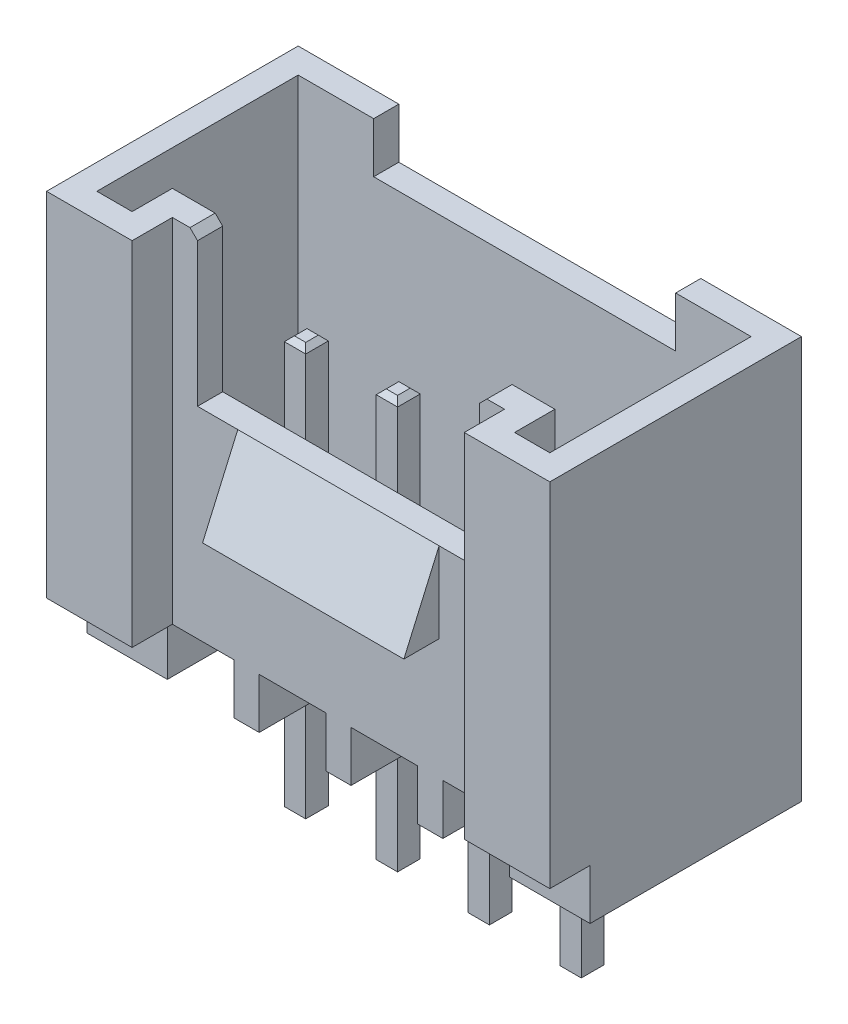
SolidWorks part; units mm, degrees
ref_plane "Plan de face" through (0, 0, 0) normal (0, 0, 1) x (1, 0, 0)
ref_plane "Plan de dessus" through (0, 0, 0) normal (0, 1, 0) x (1, 0, 0)
ref_plane "Plan de droite" through (0, 0, 0) normal (1, 0, 0) x (0, 0, -1)
sketch "Esquisse1" plane through (0, 0, 0) normal (0, 1, 0) x (1, 0, 0)
  line L1 (0, 0) -> (10, 0)
  line L2 (0, 0) -> (0, 5)
  line L3 (0, 5) -> (10, 5)
  line L4 (10, 0) -> (10, 5)
  dimension "D1" = 5
  dimension "D2" = 10
extrude "Boss.-Extru.1" add sketch "Esquisse1" along normal blind 8
sketch "Esquisse2" plane through (0, 8, 0) normal (0, 1, 0) x (1, 0, 0)
  line L0 (0, 0) -> (10, 0) construction
  line L1 (1.7, 0) -> (8.3, 0)
  line L2 (1.7, 0) -> (1.7, 0.8)
  line L3 (1.7, 0.8) -> (8.3, 0.8)
  line L4 (8.3, 0) -> (8.3, 0.8)
  line L5 (0, 5) -> (0, 0) construction
  line L6 (10, 0) -> (10, 5) construction
  dimension "D1" = 1.7
  dimension "D2" = 1.7
  dimension "D3" = 0.8
extrude "Enlèv. mat.-Extru.1" cut sketch "Esquisse2" against normal blind 8
sketch "Esquisse4" plane through (0, 8, 0) normal (0, 1, 0) x (1, 0, 0)
  line L16 (0.5, 0.5) -> (1.2, 0.5)
  line L17 (1.2, 0.5) -> (1.2, 1.3)
  line L18 (1.2, 1.3) -> (8.8, 1.3)
  line L19 (8.8, 1.3) -> (8.8, 0.5)
  line L20 (8.8, 0.5) -> (9.5, 0.5)
  line L21 (9.5, 0.5) -> (9.5, 4.5)
  line L22 (9.5, 4.5) -> (0.5, 4.5)
  line L23 (0.5, 4.5) -> (0.5, 0.5)
  line L24 (0.5, 0.5) -> (1.2, 0.5)
  line L25 (1.2, 0.5) -> (1.2, 1.3)
  line L26 (1.2, 1.3) -> (8.8, 1.3)
  line L27 (8.8, 1.3) -> (8.8, 0.5)
  line L28 (8.8, 0.5) -> (9.5, 0.5)
  line L29 (9.5, 0.5) -> (9.5, 4.5)
  line L30 (9.5, 4.5) -> (0.5, 4.5)
  line L31 (0.5, 4.5) -> (0.5, 0.5)
  dimension "D1" = 0.5
extrude "Enlèv. mat.-Extru.2" cut sketch "Esquisse4" against normal blind 6.5
sketch "Esquisse5" plane through (0, 8, 0) normal (0, 1, 0) x (1, 0, 0)
  line L0 (10, 5) -> (0, 5) construction
  line L1 (2, 5) -> (8, 5)
  line L2 (2, 5) -> (2, 4.5)
  line L3 (2, 4.5) -> (8, 4.5)
  line L4 (8, 5) -> (8, 4.5)
  line L5 (9.5, 4.5) -> (0.5, 4.5) construction
  line L6 (10, 0) -> (10, 5) construction
  line L7 (0, 5) -> (0, 0) construction
  dimension "D1" = 2
  dimension "D2" = 2
extrude "Enlèv. mat.-Extru.3" cut sketch "Esquisse5" against normal blind 1
sketch "Esquisse6" plane through (0, 8, 0) normal (0, 1, 0) x (1, 0, 0)
  line L0 (1.2, 1.3) -> (8.8, 1.3) construction
  line L1 (2.2, 1.3) -> (7.8, 1.3)
  line L2 (2.2, 1.3) -> (2.2, 0.8)
  line L3 (2.2, 0.8) -> (7.8, 0.8)
  line L4 (7.8, 1.3) -> (7.8, 0.8)
  line L5 (8.3, 0.8) -> (1.7, 0.8) construction
  line L6 (10, 0) -> (10, 5) construction
  line L7 (0, 5) -> (0, 0) construction
  dimension "D1" = 2.2
  dimension "D2" = 2.2
extrude "Enlèv. mat.-Extru.4" cut sketch "Esquisse6" against normal blind 3
sketch "Esquisse7" plane through (10, 0, 0) normal (1, 0, 0) x (0, 0, -1)
  line L1 (0, 0) -> (0.8, 0)
  line L2 (0, 0) -> (0, 1)
  line L3 (0, 1) -> (0.8, 1)
  line L4 (0.8, 0) -> (0.8, 1)
  dimension "D1" = 0.8
  dimension "D2" = 1
extrude "Enlèv. mat.-Extru.5" cut sketch "Esquisse7" against normal blind 10
sketch "Esquisse8" plane through (0, 0, 0) normal (0, -1, 0) x (1, 0, 0)
  line L0 (10, -0.8) -> (0, -0.8) construction
  line L1 (1.6, -0.8) -> (8.4, -0.8)
  line L2 (1.6, -0.8) -> (1.6, -5)
  line L3 (1.6, -5) -> (8.4, -5)
  line L4 (8.4, -0.8) -> (8.4, -5)
  line L5 (10, -5) -> (0, -5) construction
  line L6 (0, -5) -> (0, -0.8) construction
  line L7 (10, -0.8) -> (10, -5) construction
  dimension "D1" = 1.6
  dimension "D2" = 1.6
extrude "Enlèv. mat.-Extru.6" cut sketch "Esquisse8" against normal blind 1
sketch "Esquisse9" plane through (1.6, 0, 0) normal (1, 0, 0) x (0, 0, -1)
  line L0 (5, 1) -> (0.8, 1) construction
  line L1 (4.7, 1) -> (3.9, 0.2)
  line L2 (3.9, 0.2) -> (1.9, 0.2)
  line L3 (1.9, 0.2) -> (1.1, 1)
  line L4 (0.8, 0) -> (5, 0) construction
  line L5 (4.7, 1) -> (1.1, 1)
  dimension "D1" = 45
  dimension "D2" = 45
  dimension "D3" = 0.2
  dimension "D4" = 0.3
  dimension "D5" = 0.3
extrude "Boss.-Extru.2" add sketch "Esquisse9" along normal blind 6.8
ref_plane "Plan1" through (5, 0, 0) normal (1, 0, 0) x (0, 0, -1)
sketch "Esquisse11" plane through (5, 0, 0) normal (1, 0, 0) x (0, 0, -1)
  line L0 (0.8, 5) -> (0.1, 3.4)
  line L1 (0.1, 3.4) -> (0.8, 3.4)
  line L2 (0.8, 1) -> (0.8, 8) construction
  line L3 (0.8, 3.4) -> (0.8, 5)
  dimension "D1" = 1.6
  dimension "D2" = 0.7
extrude "Boss.-Extru.3" add sketch "Esquisse11" along normal blind 2 and the other way blind 2
ref_plane "Plan2" through (0, 1, 0) normal (0, 1, 0) x (1, 0, 0)
sketch "Esquisse12" plane through (0, 1, 0) normal (0, 1, 0) x (1, 0, 0)
  line L0 (8.3, 0.8) -> (1.7, 0.8) construction
  line L1 (1.6, 5) -> (8.4, 5) construction
  line L2 (3, 0.8) -> (7, 0.8) construction
  line L3 (4.75, 0.8) -> (5.25, 0.8)
  line L4 (4.75, 0.8) -> (4.75, 5)
  line L5 (4.75, 5) -> (5.25, 5)
  line L6 (5.25, 0.8) -> (5.25, 5)
  line L8 (2.925, 0.8) -> (3.425, 0.8)
  line L9 (2.925, 0.8) -> (2.925, 5)
  line L10 (2.925, 5) -> (3.425, 5)
  line L11 (3.425, 0.8) -> (3.425, 5)
  line L12 (6.575, 0.8) -> (7.075, 0.8)
  line L13 (6.575, 0.8) -> (6.575, 5)
  line L14 (6.575, 5) -> (7.075, 5)
  line L15 (7.075, 0.8) -> (7.075, 5)
  line L16 (3.175, 0.8) -> (3.175, 5) construction
  line L17 (6.825, 0.8) -> (6.825, 5) construction
  point P0 (5, 0.8)
  point P1 (5, 5)
  point P26 (6.2379, 5.3568)
  point P27 (6.2497, 5)
  dimension "D1" = 0.5
  dimension "D2" = 0.25
  dimension "D3" = 0.5
  dimension "D4" = 0.5
  dimension "D5" = 0.25
  dimension "D6" = 0.25
  dimension "D7" = 1.575
  dimension "D8" = 1.575
extrude "Boss.-Extru.4" add sketch "Esquisse12" against normal blind 1
chamfer "Chanfrein1" distance 0.15 angle 45 2 edges at (2.2, 8, -1.05) (7.8, 8, -1.05)
sketch "Esquisse13" plane through (0, 0.2, 0) normal (0, -1, 0) x (1, 0, 0)
  line L0 (5, -0.8) -> (5, -5) construction
  line L1 (2.05, -2.675) -> (2.475, -2.675)
  line L2 (2.05, -2.675) -> (2.05, -3.125)
  line L3 (2.05, -3.125) -> (2.475, -3.125)
  line L4 (2.475, -2.675) -> (2.475, -3.125)
  line L5 (4.3, -3.125) -> (3.875, -3.125)
  line L6 (3.875, -2.675) -> (3.875, -3.125)
  line L7 (4.3, -2.675) -> (4.3, -3.125)
  line L8 (4.3, -2.675) -> (3.875, -2.675)
  line L9 (4.75, -0.8) -> (5.25, -0.8) construction
  line L10 (5.25, -5) -> (4.75, -5) construction
  line L11 (1.6, -0.8) -> (1.6, -5) construction
  line L12 (2.925, -5) -> (2.925, -0.8) construction
  line L14 (2.05, -2.9) -> (2.475, -2.9) construction
  line L15 (2.925, -1.9) -> (1.6, -1.9) construction
  line L16 (3.175, -0.8) -> (3.175, -5) construction
  line L17 (2.925, -0.8) -> (3.425, -0.8) construction
  line L18 (3.425, -5) -> (2.925, -5) construction
  line L19 (5.7, -3.125) -> (6.125, -3.125)
  line L20 (5.7, -2.675) -> (5.7, -3.125)
  line L21 (5.7, -2.675) -> (6.125, -2.675)
  line L22 (6.125, -2.675) -> (6.125, -3.125)
  line L23 (7.525, -2.675) -> (7.525, -3.125)
  line L24 (7.95, -3.125) -> (7.525, -3.125)
  line L25 (7.95, -2.675) -> (7.95, -3.125)
  line L26 (7.95, -2.675) -> (7.525, -2.675)
  dimension "D1" = 0.45
  dimension "D2" = 0.45
  dimension "D3" = 0.45
  dimension "D4" = 1
extrude "Boss.-Extru.5" add sketch "Esquisse13" along normal blind 3.2 and the other way blind 5
chamfer "Chanfrein2" distance 0.1 angle 45 32 edges at (2.2625, -3, -3.125) (2.475, -3, -2.9) (2.05, -3, -2.9) (2.2625, -3, -2.675) (4.0875, -3, -3.125) (4.3, -3, -2.9) (4.0875, -3, -2.675) (3.875, -3, -2.9) (5.9125, -3, -3.125) (6.125, -3, -2.9) (5.9125, -3, -2.675) (5.7, -3, -2.9) (7.7375, -3, -3.125) (7.95, -3, -2.9) (7.525, -3, -2.9) (7.7375, -3, -2.675) (7.7375, 5.2, -2.675) (7.95, 5.2, -2.9) (7.525, 5.2, -2.9) (7.7375, 5.2, -3.125) (5.9125, 5.2, -2.675) (6.125, 5.2, -2.9) (5.9125, 5.2, -3.125) (5.7, 5.2, -2.9) (4.0875, 5.2, -2.675) (4.3, 5.2, -2.9) (4.0875, 5.2, -3.125) (3.875, 5.2, -2.9) (2.05, 5.2, -2.9) (2.2625, 5.2, -3.125) (2.475, 5.2, -2.9) (2.2625, 5.2, -2.675)
